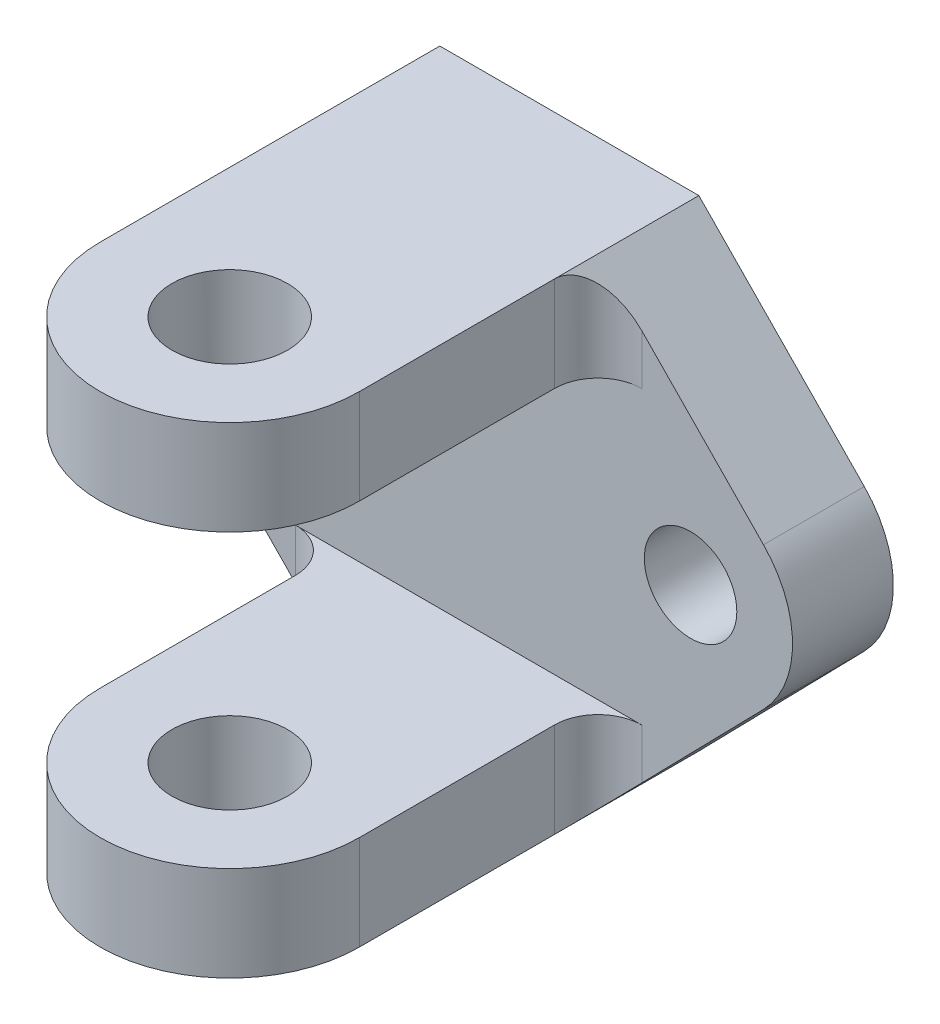
SolidWorks part; units mm, degrees
material "7075-T6 (SN)"
ref_plane "Front Plane" through (0, 0, 0) normal (0, 0, 1) x (1, 0, 0)
ref_plane "Top Plane" through (0, 0, 0) normal (0, 1, 0) x (1, 0, 0)
ref_plane "Right Plane" through (0, 0, 0) normal (1, 0, 0) x (0, 0, -1)
sketch "Sketch1" plane through (0, 0, 0) normal (0, 0, 1) x (1, 0, 0)
  line L0 (15.24, 0) -> (-15.24, 0) construction
  line L1 (-23.24, -16.51) -> (23.24, -16.51)
  line L2 (-23.24, -16.51) -> (-23.24, 16.51)
  line L3 (-23.24, 16.51) -> (23.24, 16.51)
  line L4 (23.24, -16.51) -> (23.24, 16.51)
  line L5 (-23.24, -16.51) -> (23.24, 16.51) construction
  line L6 (-23.24, 16.51) -> (23.24, -16.51) construction
  circle A0 centre (15.24, 0) radius 3.175
  circle A1 centre (-15.24, 0) radius 3.175
  point P0 (0, 0)
  dimension "D1" = 6.35
  dimension "D2" = 30.48
  dimension "D3" = 8
  dimension "D4" = 16.51
extrude "Boss-Extrude1" add sketch "Sketch1" along normal blind 9.46 contours L3 L4 L1 L2
sketch "Sketch2" plane through (0, 0, 9.46) normal (0, 0, 1) x (1, 0, 0)
  line L0 (-15.24, 0) -> (15.24, 0) construction
  line L2 (-23.24, 10) -> (23.24, 10)
  line L3 (-23.24, 10) -> (-23.24, 16.51)
  line L4 (-23.24, 16.51) -> (23.24, 16.51)
  line L5 (23.24, 10) -> (23.24, 16.51)
  line L6 (-23.24, 10) -> (23.24, 16.51) construction
  line L7 (-23.24, 16.51) -> (23.24, 10) construction
  line L8 (-23.24, 16.51) -> (-23.24, -16.51) construction
  line L9 (23.24, -10) -> (23.24, -16.51)
  line L10 (-23.24, -10) -> (-23.24, -16.51)
  line L11 (-23.24, -16.51) -> (23.24, -10) construction
  line L12 (-23.24, -10) -> (23.24, -16.51) construction
  line L13 (-23.24, -10) -> (23.24, -10)
  line L14 (-23.24, -16.51) -> (23.24, -16.51)
  circle A0 centre (-15.24, 0) radius 3.175 construction
  circle A1 centre (15.24, 0) radius 3.175 construction
  point P6 (0, 13.255)
  point P21 (0, -13.255)
  dimension "D1" = 20
extrude "Boss-Extrude2" add sketch "Sketch2" along normal blind 53
sketch "Sketch3" plane through (0, 0, 0) normal (0, 1, 0) x (1, 0, 0)
  point P0 (0, -25.8481)
  dimension "D1" = 25.8481
ref_point "UBJ Point"
sketch "Sketch4" plane through (0, 0, 0) normal (0, 1, 0) x (1, 0, 0)
  circle A0 centre (0, -25.8481) radius 3.9688
  dimension "D1" = 7.9375
extrude "Cut-Extrude1" cut sketch "Sketch4" against normal up to surface and the other way up to surface up to face at (0, -16.51, 31.23) other way up to face at (0, 16.51, 31.23)
sketch "Sketch5" plane through (0, 0, 0) normal (0, 1, 0) x (1, 0, 0)
  line L0 (23.24, -9.46) -> (8.2363, -31.4641)
  line L1 (-8.2363, -31.4641) -> (-23.24, -9.46)
  line L4 (23.24, 0) -> (-23.24, 0)
  line L5 (-23.24, 0) -> (-23.24, -62.46)
  line L6 (-23.24, -62.46) -> (23.24, -62.46)
  line L7 (23.24, -62.46) -> (23.24, 0)
  line L9 (-23.24, -9.46) -> (-23.24, -62.46)
  line L10 (-23.24, -62.46) -> (23.24, -62.46)
  line L11 (23.24, -62.46) -> (23.24, -9.46)
  line L12 (23.24, -9.46) -> (-23.24, -9.46)
  line L13 (23.24, -62.46) -> (23.24, -9.46)
  line L14 (-23.24, -62.46) -> (23.24, -62.46)
  line L15 (-23.24, -9.46) -> (-23.24, -62.46)
  line L17 (23.24, -62.46) -> (23.24, -9.46)
  line L18 (-23.24, -62.46) -> (23.24, -62.46)
  line L19 (-23.24, -9.46) -> (-23.24, -62.46)
  arc A0 (-8.2363, -31.4641) -> (8.2363, -31.4641) centre (0, -25.8481) ccw
  circle A1 centre (0, -25.8481) radius 3.9688 construction
  circle A2 centre (0, -25.8481) radius 3.9688 construction
  dimension "D3" = 6
  dimension "D1" = 0
  dimension "D2" = 0
extrude "Cut-Extrude2" [suppressed] cut sketch "Sketch5" against normal up to surface and the other way up to surface contours A0 L1 L9 L10 L11 L0
sketch "Sketch6" plane through (0, 0, 0) normal (0, 1, 0) x (1, 0, 0)
  line L0 (-8.89, -25.8481) -> (-8.89, -17.46)
  line L1 (8.89, -25.8481) -> (8.89, -17.46)
  line L2 (-16.89, -9.46) -> (-23.24, -9.46)
  line L3 (-8.89, -17.46) -> (-8.89, -9.46)
  line L4 (23.24, -9.46) -> (-23.24, -9.46)
  line L5 (-23.24, -9.46) -> (-23.24, -62.46)
  line L6 (-23.24, -62.46) -> (23.24, -62.46)
  line L7 (23.24, -62.46) -> (23.24, -9.46)
  line L8 (23.24, -9.46) -> (16.89, -9.46)
  line L9 (-23.24, -9.46) -> (-23.24, -62.46)
  line L10 (-23.24, -62.46) -> (23.24, -62.46)
  line L11 (23.24, -62.46) -> (23.24, -9.46)
  line L12 (-8.89, -9.46) -> (-16.89, -9.46)
  line L13 (8.89, -17.46) -> (8.89, -9.46)
  line L14 (8.89, -9.46) -> (16.89, -9.46)
  arc A0 (-8.89, -25.8481) -> (8.89, -25.8481) centre (0, -25.8481) ccw
  circle A1 centre (0, -25.8481) radius 3.9688 construction
  arc A2 (-8.89, -17.46) -> (-16.89, -9.46) centre (-16.89, -17.46) ccw construction
  arc A3 (8.89, -17.46) -> (16.89, -9.46) centre (16.89, -17.46) cw construction
  dimension "D2" = 8.89
  dimension "D3" = 8
  dimension "D1" = 0
extrude "Cut-Extrude3" cut sketch "Sketch6" against normal up to surface and the other way up to surface
fillet "Fillet1" [suppressed] radius 12.7
sketch "Sketch7" plane through (0, 0, 0) normal (0, 0, 1) x (1, 0, 0)
  line L0 (-15.24, 7) -> (-8.89, 7)
  line L1 (-15.24, -7) -> (-8.89, -7)
  line L2 (-8.89, 10) -> (-8.89, 7)
  line L3 (-8.89, -10) -> (-8.89, -7)
  line L4 (0, 10.3988) -> (0, -8.4154) construction
  line L5 (8.89, -10) -> (8.89, -7)
  line L6 (8.89, 10) -> (8.89, 16.51)
  line L7 (23.24, 16.51) -> (23.24, -16.51)
  line L8 (8.89, -10) -> (8.89, -16.51)
  line L9 (8.89, 10) -> (8.89, 7)
  line L10 (15.24, 7) -> (8.89, 7)
  line L11 (15.24, -7) -> (8.89, -7)
  line L12 (8.89, 10) -> (-8.89, 10)
  line L15 (-23.24, 16.51) -> (-23.24, -16.51)
  line L18 (-8.89, -10) -> (8.89, -10)
  line L21 (23.24, -16.51) -> (23.24, 16.51)
  line L27 (-23.24, 16.51) -> (-23.24, -16.51)
  line L33 (23.24, -16.51) -> (23.24, 16.51)
  line L36 (-8.89, 16.51) -> (-8.89, 10)
  line L37 (-8.89, -10) -> (-8.89, -16.51)
  line L48 (-8.89, 10) -> (-8.89, 16.51)
  line L49 (-8.89, -16.51) -> (-8.89, -10)
  line L52 (-8.89, 16.51) -> (-23.24, 16.51)
  line L53 (-8.89, 16.51) -> (-23.24, 16.51)
  line L54 (-23.24, -16.51) -> (-8.89, -16.51)
  line L55 (-23.24, -16.51) -> (-8.89, -16.51)
  line L56 (8.89, -10) -> (8.89, -16.51)
  line L57 (8.89, -16.51) -> (23.24, -16.51)
  line L58 (8.89, -16.51) -> (23.24, -16.51)
  line L59 (23.24, 16.51) -> (8.89, 16.51)
  line L60 (23.24, 16.51) -> (8.89, 16.51)
  line L61 (8.89, 16.51) -> (8.89, 10)
  arc A0 (-15.24, 7) -> (-15.24, -7) centre (-15.24, 0) ccw
  circle A1 centre (-15.24, 0) radius 3.175 construction
  arc A2 (15.24, 7) -> (15.24, -7) centre (15.24, 0) cw
  dimension "D2" = 7
  dimension "D1" = 0
extrude "Cut-Extrude4" cut sketch "Sketch7" along normal up to surface (9.46 mm away)
fillet "Fillet2" [suppressed] radius 5
sketch "Sketch8" plane through (0, 0, 0) normal (0, 0, 1) x (1, 0, 0)
  line L0 (15.24, 7) -> (8.89, 7) construction
  line L1 (8.89, 16.51) -> (8.89, 7) construction
  line L2 (15.24, 7) -> (8.89, 7)
  line L3 (8.89, 16.51) -> (8.89, 7)
  line L4 (6.7586, 0) -> (-5.803, 0) construction
  line L5 (0, 7.1591) -> (0, -7.1591) construction
  line L6 (8.89, 16.51) -> (20.2457, 4.8932)
  line L7 (-8.89, 16.51) -> (-8.89, 7)
  line L8 (-15.24, 7) -> (-8.89, 7)
  line L9 (-8.89, 16.51) -> (-20.2457, 4.8932)
  line L10 (-8.89, -16.51) -> (-20.2457, -4.8932)
  line L11 (-15.24, -7) -> (-8.89, -7)
  line L12 (-8.89, -16.51) -> (-8.89, -7)
  line L13 (8.89, -16.51) -> (8.89, -7)
  line L14 (15.24, -7) -> (8.89, -7)
  line L15 (8.89, -16.51) -> (20.2457, -4.8932)
  arc A0 (15.24, -7) -> (15.24, 7) centre (15.24, 0) ccw construction
  arc A1 (20.2457, 4.8932) -> (15.24, 7) centre (15.24, 0) ccw
  arc A2 (-20.2457, 4.8932) -> (-15.24, 7) centre (-15.24, 0) cw
  arc A3 (-20.2457, -4.8932) -> (-15.24, -7) centre (-15.24, 0) ccw
  arc A4 (20.2457, -4.8932) -> (15.24, -7) centre (15.24, 0) cw
extrude "Boss-Extrude3" add sketch "Sketch8" along normal up to surface (9.46 mm away) contours L15 A4 L14 L13 | A3 L10 L12 L11 | L6 A1 L2 L3 | L9 A2 L8 L7 up to face at (0, 0, 9.46)
fillet "Fillet3" radius 3 4 edges at (8.89, 13.255, 9.46) (-8.89, 13.255, 9.46) (-8.89, -13.255, 9.46) (8.89, -13.255, 9.46)
sketch "Sketch10" plane through (0, 0, 0) normal (0, 0, 1) x (1, 0, 0)
  line L5 (-8.89, 16.51) -> (-20.2457, 4.8932)
  line L6 (-8.89, 16.51) -> (-20.2457, 4.8932)
  line L7 (8.89, 16.51) -> (-8.89, 16.51)
  line L8 (20.2457, 4.8932) -> (8.89, 16.51)
  line L9 (8.89, -16.51) -> (20.2457, -4.8932)
  line L10 (-8.89, -16.51) -> (8.89, -16.51)
  line L13 (8.89, 16.51) -> (-8.89, 16.51)
  line L14 (20.2457, 4.8932) -> (8.89, 16.51)
  line L15 (8.89, -16.51) -> (20.2457, -4.8932)
  line L16 (-8.89, -16.51) -> (8.89, -16.51)
  line L18 (-20.2457, -4.8932) -> (-8.89, -16.51)
  line L19 (-20.2457, -4.8932) -> (-8.89, -16.51)
  arc A2 (-20.2457, 4.8932) -> (-20.2457, -4.8932) centre (-15.24, 0) ccw
  arc A3 (20.2457, -4.8932) -> (20.2457, 4.8932) centre (15.24, 0) ccw
  arc A5 (20.2457, -4.8932) -> (20.2457, 4.8932) centre (15.24, 0) ccw
  arc A6 (-20.2457, 4.8932) -> (-20.2457, -4.8932) centre (-15.24, 0) ccw
  dimension "D1" = 0
extrude "Cut-Extrude5" cut sketch "Sketch10" along normal blind 2.54
